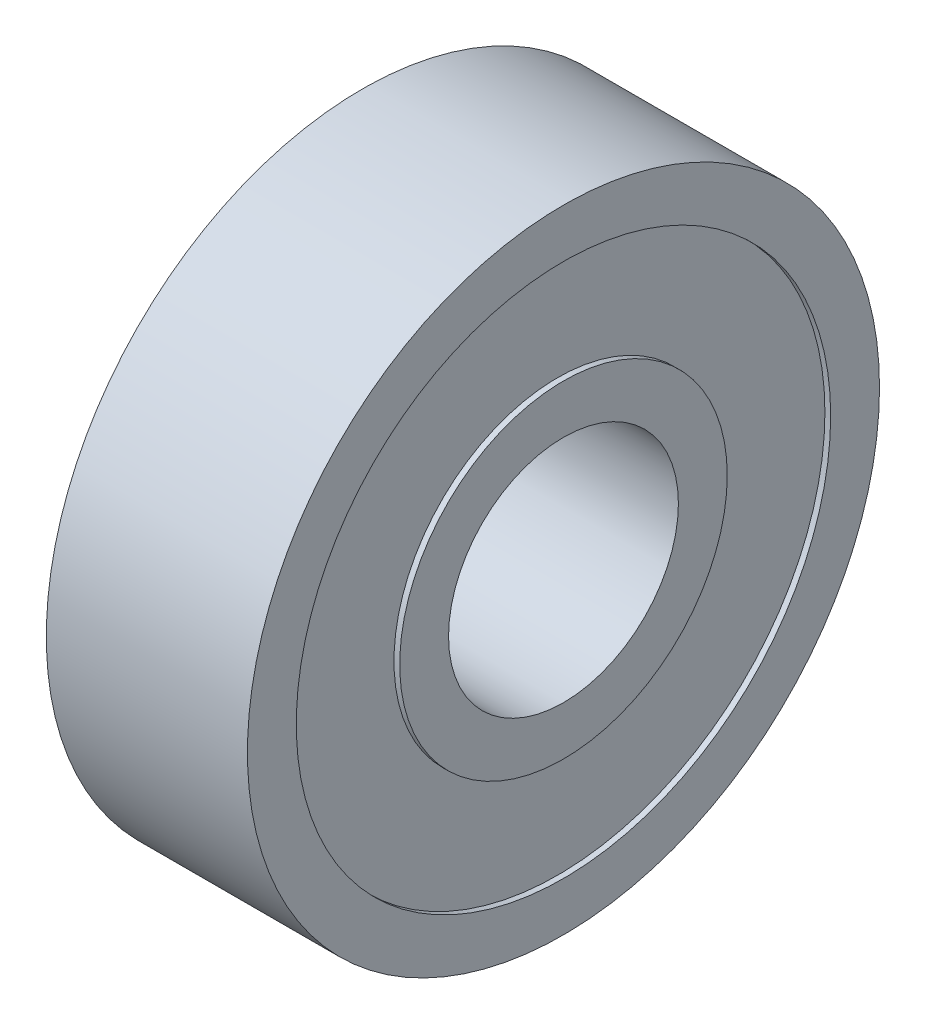
SolidWorks part; units mm, degrees
ref_plane "Plan de face" through (0, 0, 0) normal (0, 0, 1) x (1, 0, 0)
ref_plane "Plan de dessus" through (0, 0, 0) normal (0, 1, 0) x (1, 0, 0)
ref_plane "Plan de droite" through (0, 0, 0) normal (1, 0, 0) x (0, 0, -1)
sketch "Esquisse1" plane through (0, 0, 0) normal (1, 0, 0) x (0, 0, -1)
  circle A0 centre (0, 0) radius 4
  circle A1 centre (0, 0) radius 11
  dimension "D1" = 8
  dimension "D2" = 22
extrude "Boss.-Extru.1" add sketch "Esquisse1" along normal mid plane 7
sketch "Esquisse2" plane through (3.5, 0, 0) normal (1, 0, 0) x (0, 0, -1)
  circle A0 centre (0, 0) radius 9.3
  circle A1 centre (0, 0) radius 11 construction
  circle A2 centre (0, 0) radius 5.7
  circle A3 centre (0, 0) radius 4 construction
  dimension "D1" = 1.7
  dimension "D2" = 1.7
extrude "Enlèv. mat.-Extru.1" cut sketch "Esquisse2" against normal blind 0.2
mirror "Symétrie1" about plane through (0, 0, 0) normal (1, 0, 0) of "Enlèv. mat.-Extru.1"
